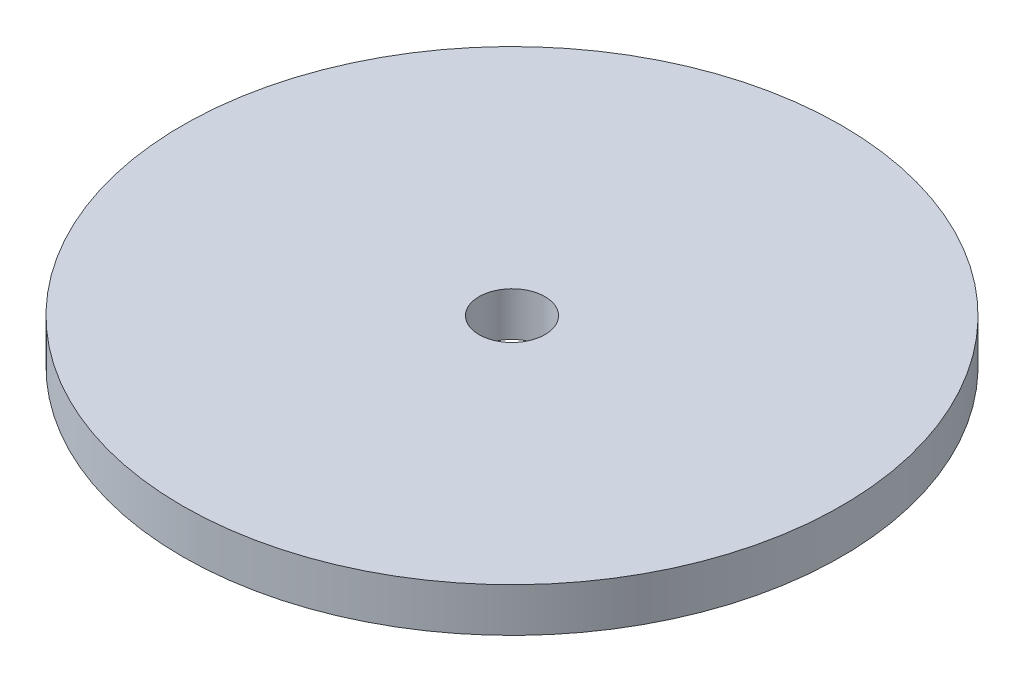
SolidWorks part; units mm, degrees
ref_plane "Front" through (0, 0, 0) normal (0, 0, 1) x (1, 0, 0)
ref_plane "Top" through (0, 0, 0) normal (0, 1, 0) x (1, 0, 0)
ref_plane "Right" through (0, 0, 0) normal (1, 0, 0) x (0, 0, -1)
sketch "Skizze1" plane through (0, 0, 0) normal (0, 1, 0) x (1, 0, 0)
  circle A0 centre (0, 0) radius 75
  circle A1 centre (0, 0) radius 7.5
  dimension "D1" = 15
  dimension "D2" = 150
extrude "Aufsatz-Linear austragen1" add sketch "Skizze1" along normal blind 10
